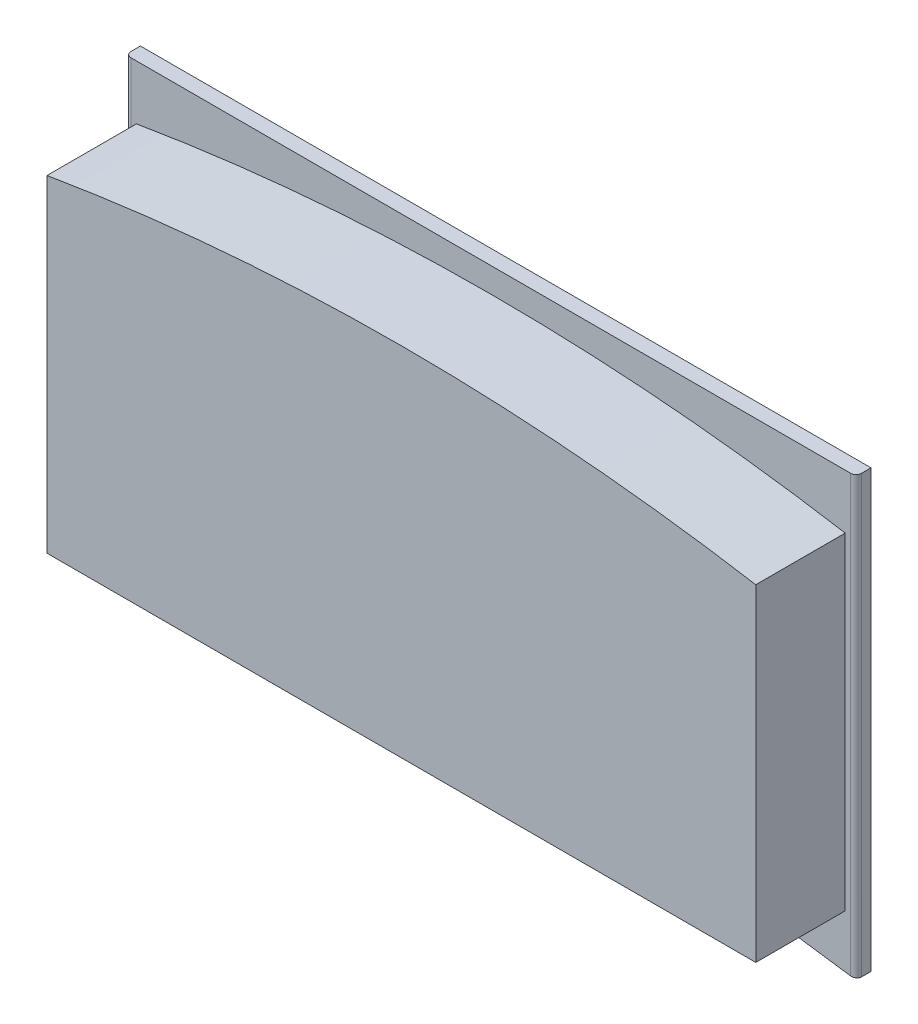
SolidWorks part; units mm, degrees
material "AISI 1020"
ref_plane "Front Plane" through (0, 0, 0) normal (0, 0, 1) x (1, 0, 0)
ref_plane "Top Plane" through (0, 0, 0) normal (0, 1, 0) x (1, 0, 0)
ref_plane "Right Plane" through (0, 0, 0) normal (1, 0, 0) x (0, 0, -1)
sketch "Sketch1" plane through (0, 0, 0) normal (0, 0, 1) x (1, 0, 0)
  line L0 (-33.5, 20) -> (-33.5, -20)
  line L2 (33.5, -20) -> (33.5, 20)
  line L4 (-32.8097, 0) -> (36.7903, 0) construction
  line L5 (-33.5, 20) -> (33.5, 20)
  line L6 (0, 28.6482) -> (0, -30.6988) construction
  arc A1 (-33.5, -20) -> (33.5, -20) centre (0, -237.4345) cw
  point P5 (-33.5, 0)
  point P10 (0, 20)
  point P12 (0, -17.4345)
  dimension "D1" = 33.5
  dimension "D3" = 220
  dimension "D2" = 20
extrude "Boss-Extrude1" add sketch "Sketch1" along normal blind 1.3667
ref_plane "Plane1" through (0, 0, 1.3667) normal (0, 0, 1) x (1, 0, 0)
sketch "Sketch2" plane through (0, 0, 1.3667) normal (0, 0, 1) x (1, 0, 0)
  line L1 (32.5, -15) -> (-32.5, -15)
  line L2 (32.5, -15) -> (32.5, 15)
  line L4 (-32.5, -15) -> (-32.5, 15)
  arc A0 (-32.5, 15) -> (32.5, 15) centre (0, -177.2726) cw
  point P0 (0, 0)
  point P6 (0, 17.7274)
  point P9 (0, -15)
  point P11 (-32.5, 0)
  dimension "D1" = 195
  dimension "D2" = 65
  dimension "D3" = 15
extrude "Boss-Extrude2" add sketch "Sketch2" along normal blind 8.2 contours A0 L2 L1 L4
fillet "Fillet1" radius 0.5 2 edges at (33.5, 0, 1.3667) (-33.5, 0, 1.3667)
